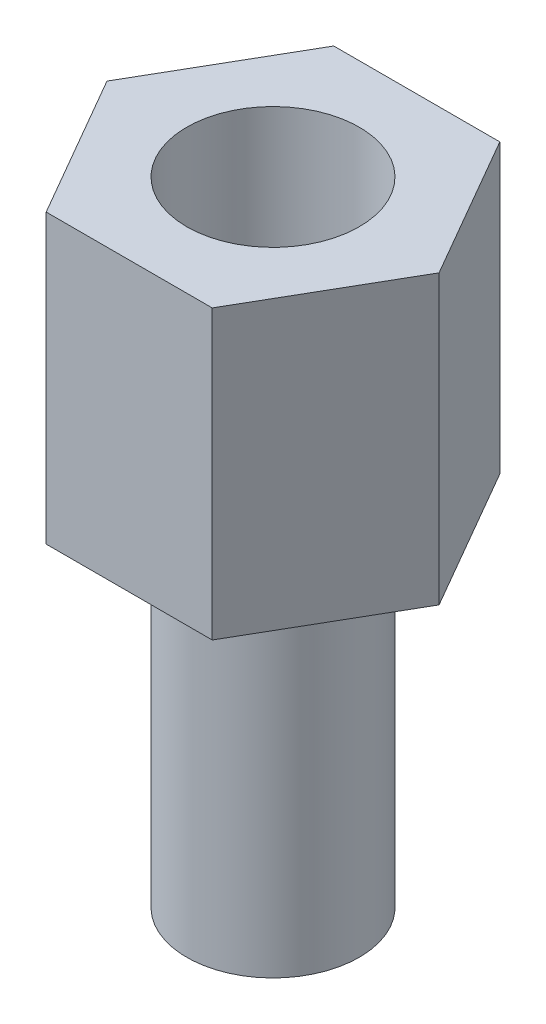
SolidWorks part; units mm, degrees
material "ABS"
ref_plane "Alzado" through (0, 0, 0) normal (0, 0, 1) x (1, 0, 0)
ref_plane "Planta" through (0, 0, 0) normal (0, 1, 0) x (1, 0, 0)
ref_plane "Vista lateral" through (0, 0, 0) normal (1, 0, 0) x (0, 0, -1)
sketch "Croquis1" plane through (0, 0, 0) normal (0, 1, 0) x (1, 0, 0)
  line L1 (1.4434, -2.5) -> (2.8868, 0)
  line L2 (2.8868, 0) -> (1.4434, 2.5)
  line L3 (1.4434, 2.5) -> (-1.4434, 2.5)
  line L4 (-1.4434, 2.5) -> (-2.8868, 0)
  line L5 (-2.8868, 0) -> (-1.4434, -2.5)
  line L6 (-1.4434, -2.5) -> (1.4434, -2.5)
  circle A0 centre (0, 0) radius 2.5 construction
  circle A1 centre (0, 0) radius 1.5
  dimension "D2" = 3
  dimension "D1" = 5
extrude "Saliente-Extruir1" add sketch "Croquis1" along normal blind 5
sketch "Croquis2" plane through (0, 0, 0) normal (0, -1, 0) x (1, 0, 0)
  circle A0 centre (0, 0) radius 1.5 construction
  circle A1 centre (0, 0) radius 1.5
extrude "Saliente-Extruir2" add sketch "Croquis2" along normal blind 6 separate body
